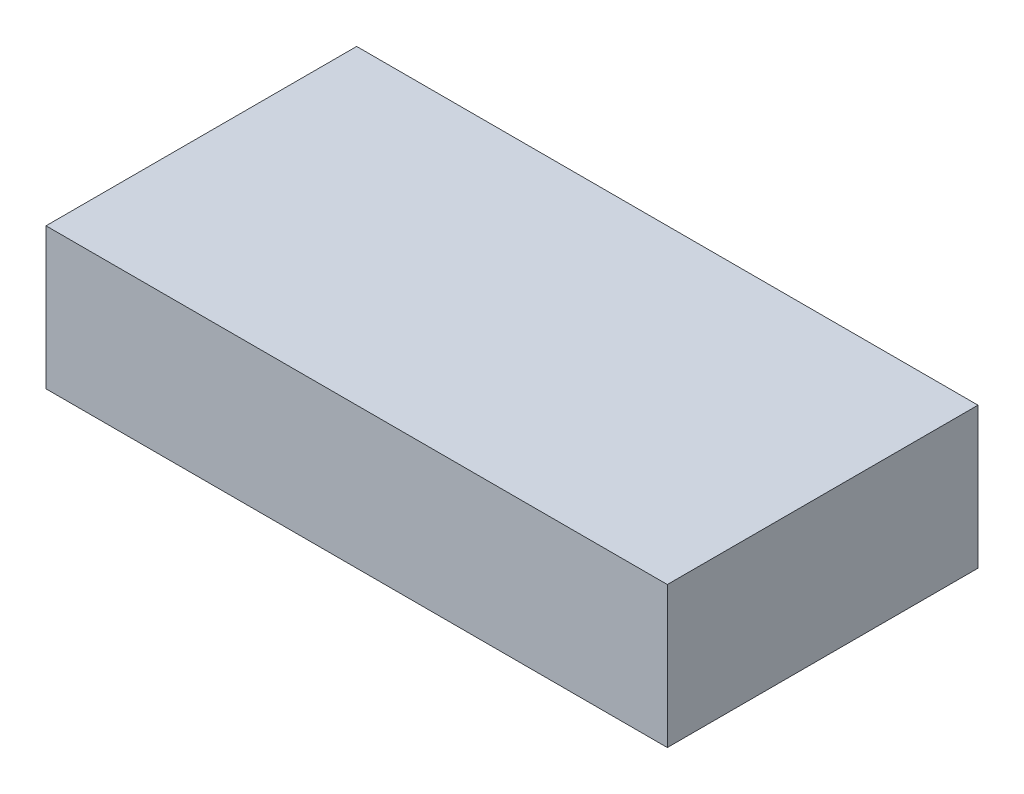
SolidWorks part; units mm, degrees
ref_plane "前视基准面" through (0, 0, 0) normal (0, 0, 1) x (1, 0, 0)
ref_plane "上视基准面" through (0, 0, 0) normal (0, 1, 0) x (1, 0, 0)
ref_plane "右视基准面" through (0, 0, 0) normal (1, 0, 0) x (0, 0, -1)
sketch "草图1" plane through (0, 0, 0) normal (0, 1, 0) x (1, 0, 0)
  line L1 (-9.3284, 4.098) -> (12.6716, 4.098)
  line L2 (-9.3284, 4.098) -> (-9.3284, -6.902)
  line L3 (-9.3284, -6.902) -> (12.6716, -6.902)
  line L4 (12.6716, 4.098) -> (12.6716, -6.902)
  dimension "D1" = 11
  dimension "D2" = 22
extrude "凸台-拉伸1" add sketch "草图1" along normal blind 5
